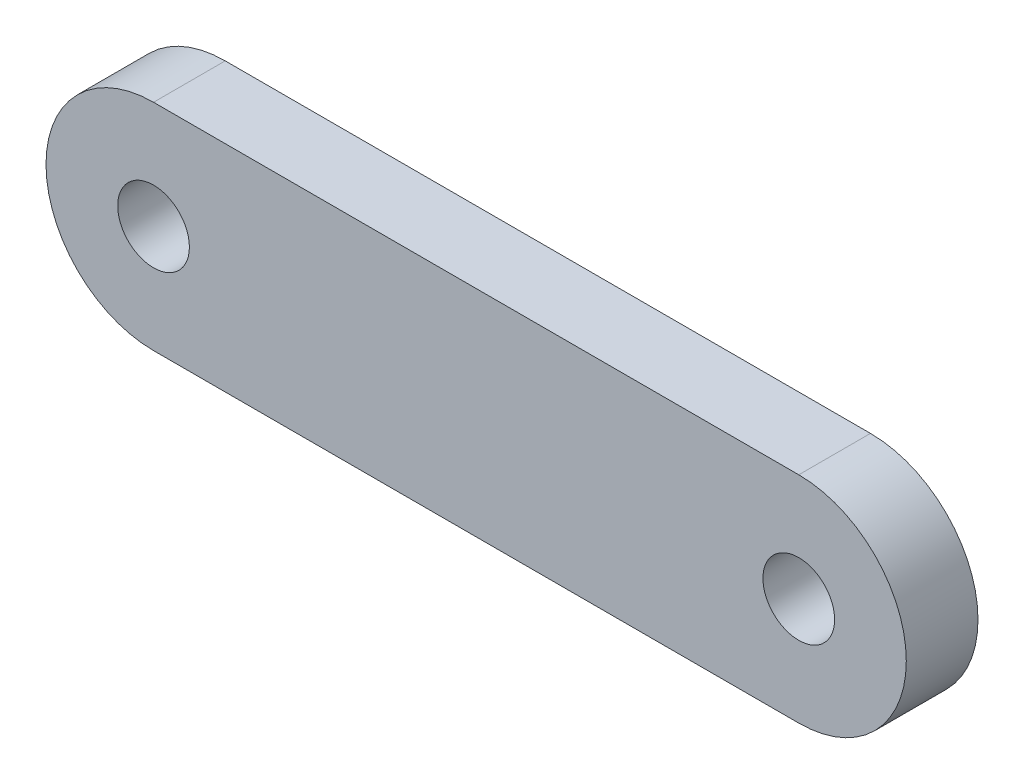
SolidWorks part; units mm, degrees
ref_plane "Front Plane" through (0, 0, 0) normal (0, 0, 1) x (1, 0, 0)
ref_plane "Top Plane" through (0, 0, 0) normal (0, 1, 0) x (1, 0, 0)
ref_plane "Right Plane" through (0, 0, 0) normal (1, 0, 0) x (0, 0, -1)
sketch "Sketch1" plane through (0, 0, 0) normal (0, 0, 1) x (1, 0, 0)
  line L0 (-45, 0) -> (45, 0) construction
  line L1 (-45, 15) -> (45, 15)
  line L2 (-45, -15) -> (45, -15)
  arc A0 (-45, 15) -> (-45, -15) centre (-45, 0) ccw
  arc A1 (45, -15) -> (45, 15) centre (45, 0) ccw
  circle A2 centre (-45, 0) radius 5
  circle A3 centre (45, 0) radius 5
  point P2 (0, 0)
  point P12 (0, -15)
  dimension "D1" = 10
  dimension "D2" = 10
  dimension "D3" = 90
  dimension "D4" = 30
extrude "Boss-Extrude1" add sketch "Sketch1" along normal blind 10
